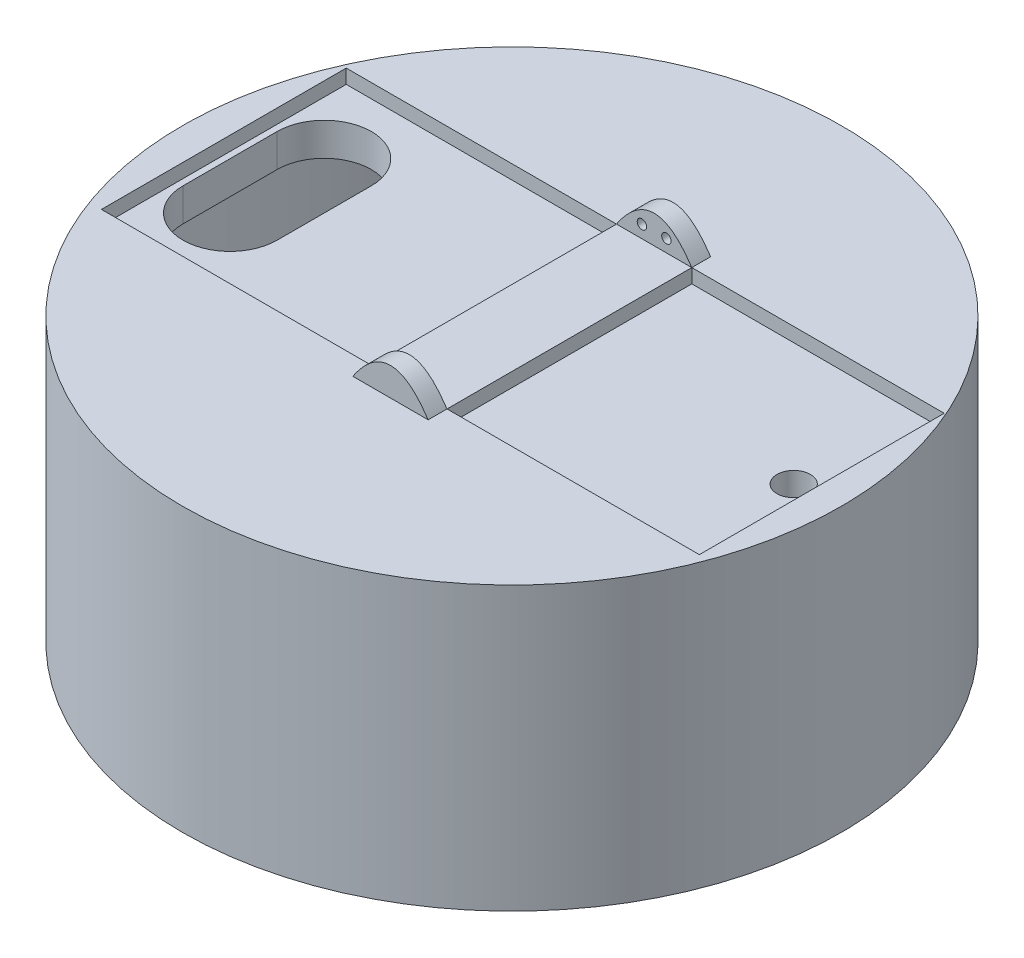
SolidWorks part; units mm, degrees
material "AISI 304"
ref_plane "Front Plane" through (0, 0, 0) normal (0, 0, 1) x (1, 0, 0)
ref_plane "Top Plane" through (0, 0, 0) normal (0, 1, 0) x (1, 0, 0)
ref_plane "Right Plane" through (0, 0, 0) normal (1, 0, 0) x (0, 0, -1)
sketch "Sketch1" plane through (0, 0, 0) normal (0, 1, 0) x (1, 0, 0)
  circle A0 centre (0, 0) radius 35
  dimension "D1" = 70
extrude "Boss-Extrude1" add sketch "Sketch1" along normal blind 30
ref_plane "Plane1" through (0, 0, 0) normal (0, -1, 0) x (-1, 0, 0)
sketch "Sketch2" plane through (0, 0, 0) normal (0, -1, 0) x (-1, 0, 0)
  circle A0 centre (0, 0) radius 33
  circle A3 centre (0, 0) radius 35 construction
  dimension "D1" = 2
extrude "Cut-Extrude1" cut sketch "Sketch2" against normal blind 25
ref_plane "Plane4" through (0, 0, -16) normal (0, 0, 1) x (1, 0, 0)
sketch "Sketch4" plane through (0, 0, -16) normal (0, 0, 1) x (1, 0, 0)
  line L0 (35, 30) -> (-35, 30) construction
  line L1 (-2.8951, 30) -> (5.1049, 30)
  spline S0 degree 2 poles (-2.8951, 30) (1.1049, 36) (5.1049, 30) knots 0 0 0 1 1 1
  point P9 (1.1049, 30)
  dimension "D1" = 8
  dimension "D2" = 3
extrude "Boss-Extrude3" add sketch "Sketch4" along normal blind 2
pattern_linear "LPattern1" count 2 spacing 28 along (0, 0, 1) of "Boss-Extrude3"
ref_plane "Plane5" through (0, 0, -1) normal (0, 0, -1) x (-1, 0, 0)
sketch "Sketch6" plane through (0, 0, -1) normal (0, 0, -1) x (-1, 0, 0)
  line L1 (-1.1049, 33) -> (-1.1049, 30) construction
  line L3 (2.8951, 30) -> (-5.1049, 30) construction
  circle A0 centre (0.1951, 31.3377) radius 0.5
  circle A1 centre (-2.4049, 31.3377) radius 0.5
  parabola Q22 (-5.1049, 30) -> (2.8951, 30) focus (-1.1049, 31.6667) apex (-1.1049, 33) construction
  dimension "D1" = 1
  dimension "D2" = 1.3
extrude "Cut-Extrude2" cut sketch "Sketch6" against normal blind 14 and the other way blind 14
ref_plane "Plane6" through (0, 30, 0) normal (0, 1, 0) x (1, 0, 0)
sketch "Sketch7" plane through (0, 30, 0) normal (0, 1, 0) x (1, 0, 0)
  line L0 (1.1049, 34.9826) -> (1.1049, -62.9826) construction
  line L1 (-31.5951, 14) -> (-2.8951, 14)
  line L2 (-31.5951, 14) -> (-31.5951, -12)
  line L3 (-31.5951, -12) -> (-2.8951, -12)
  line L4 (-2.8951, 14) -> (-2.8951, -12)
  line L6 (-2.8951, -14) -> (5.1049, -14) construction
  line L8 (5.1049, 14) -> (5.1049, -12)
  line L11 (5.1049, 14) -> (31.9049, 14)
  line L12 (31.9049, 14) -> (31.9049, -12)
  line L13 (31.9049, -12) -> (5.1049, -12)
  circle A1 centre (0, 0) radius 35 construction
  point P4 (1.1049, -14)
  dimension "D1" = 26
  dimension "D2" = 28.7
  dimension "D3" = 26.8
extrude "Cut-Extrude3" cut sketch "Sketch7" against normal blind 1.5
sketch "Sketch8" plane through (0, 30, 0) normal (0, 1, 0) x (1, 0, 0)
  line L0 (-25.9334, 6) -> (-25.9334, -4) construction
  line L1 (-20.9334, 6) -> (-20.9334, -4)
  line L2 (-30.9334, 6) -> (-30.9334, -4)
  line L3 (-2.8951, -12) -> (-2.8951, 14) construction
  line L5 (-2.8951, -12) -> (-2.8951, 14) construction
  arc A0 (-20.9334, 6) -> (-30.9334, 6) centre (-25.9334, 6) ccw
  arc A1 (-30.9334, -4) -> (-20.9334, -4) centre (-25.9334, -4) ccw
  point P2 (-25.9334, 1)
  point P12 (-2.8951, 1)
  dimension "D1" = 10
  dimension "D2" = 5
extrude "Cut-Extrude4" cut sketch "Sketch8" against normal blind 7
sketch "Sketch9" plane through (0, 30, 0) normal (0, 1, 0) x (1, 0, 0)
  line L0 (5.1049, 14) -> (5.1049, -12) construction
  circle A0 centre (28.9221, 1) radius 1.7757
  point P4 (5.1049, 1)
extrude "Cut-Extrude5" cut sketch "Sketch9" against normal blind 7
ref_plane "Plane8" through (0, 15, 0) normal (0, -1, 0) x (-1, 0, 0)
sketch "Sketch10" plane through (0, 15, 0) normal (0, -1, 0) x (-1, 0, 0)
  circle A0 centre (0, 0) radius 33 construction
  circle A1 centre (0, 0) radius 33
curve "Helix/Spiral1" pitch 5 height 10 turns 2
ref_plane "Plane9" through (23.3345, 15, -23.3345) normal (-0.7069, -0.0241, -0.7069) x (-0.7073, 0.0241, 0.7065)
sketch "Sketch11" plane through (23.3345, 15, -23.3345) normal (-0.7069, -0.0241, -0.7069) x (-0.7073, 0.0241, 0.7065)
  line L0 (-0.7, 2) -> (-0.7, -2)
  line L1 (-0.7, 0) -> (1.3, 0) construction
  line L2 (1.3, 0.5) -> (1.3, -0.5)
  line L3 (1.3, 0.5) -> (-0.7, 2)
  line L4 (1.3, -0.5) -> (-0.7, -2)
  point P3 (-0.7, 0)
  point P8 (1.3, 0)
  point P9 (0, 0)
  dimension "D1" = 4
  dimension "D2" = 1
  dimension "D3" = 2
  dimension "D4" = 0.7
sweep "Sweep1" add profiles "Sketch11" path "Helix/Spiral1"
